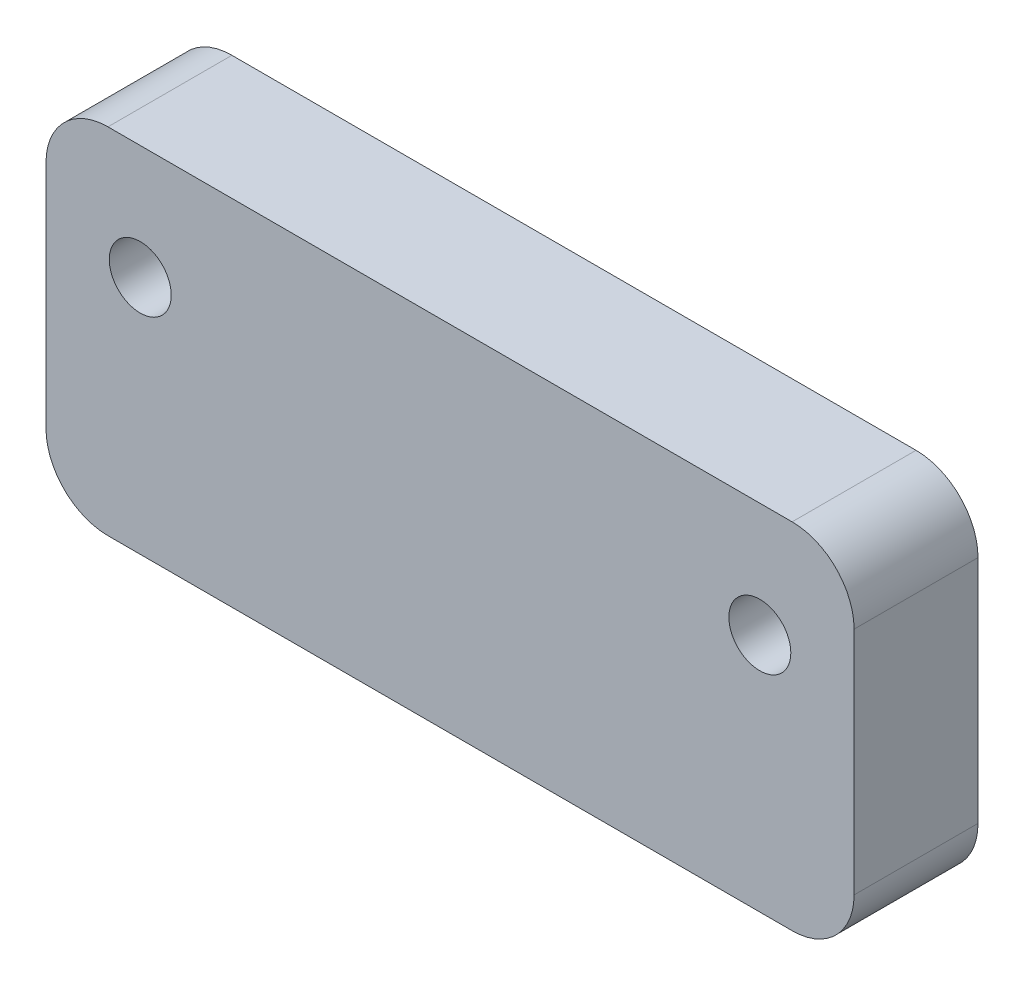
SolidWorks part; units mm, degrees
ref_plane "Front Plane" through (0, 0, 0) normal (0, 0, 1) x (1, 0, 0)
ref_plane "Top Plane" through (0, 0, 0) normal (0, 1, 0) x (1, 0, 0)
ref_plane "Right Plane" through (0, 0, 0) normal (1, 0, 0) x (0, 0, -1)
sketch "Sketch1" plane through (0, 0, 0) normal (0, 0, 1) x (1, 0, 0)
  line L1 (37.4647, -75.852) -> (92.6753, -75.852)
  line L2 (32.4647, -80.852) -> (32.4647, -99.4269)
  line L3 (37.4647, -104.4269) -> (92.6753, -104.4269)
  line L4 (97.6753, -80.852) -> (97.6753, -99.4269)
  line L5 (32.4647, -75.852) -> (97.6753, -104.4269) construction
  line L6 (32.4647, -104.4269) -> (97.6753, -75.852) construction
  circle A0 centre (90.07, -85.0656) radius 2.5 construction
  circle A1 centre (40.07, -85.0656) radius 2.5 construction
  circle A2 centre (90.07, -85.0656) radius 2.5
  circle A3 centre (40.07, -85.0656) radius 2.5
  arc A4 (32.4647, -99.4269) -> (37.4647, -104.4269) centre (37.4647, -99.4269) ccw
  arc A5 (97.6753, -99.4269) -> (92.6753, -104.4269) centre (92.6753, -99.4269) cw
  arc A6 (97.6753, -80.852) -> (92.6753, -75.852) centre (92.6753, -80.852) ccw
  arc A7 (37.4647, -75.852) -> (32.4647, -80.852) centre (37.4647, -80.852) ccw
  point P0 (65.07, -90.1395)
  dimension "D1" = 5
extrude "Boss-Extrude1" add sketch "Sketch1" along normal blind 10
